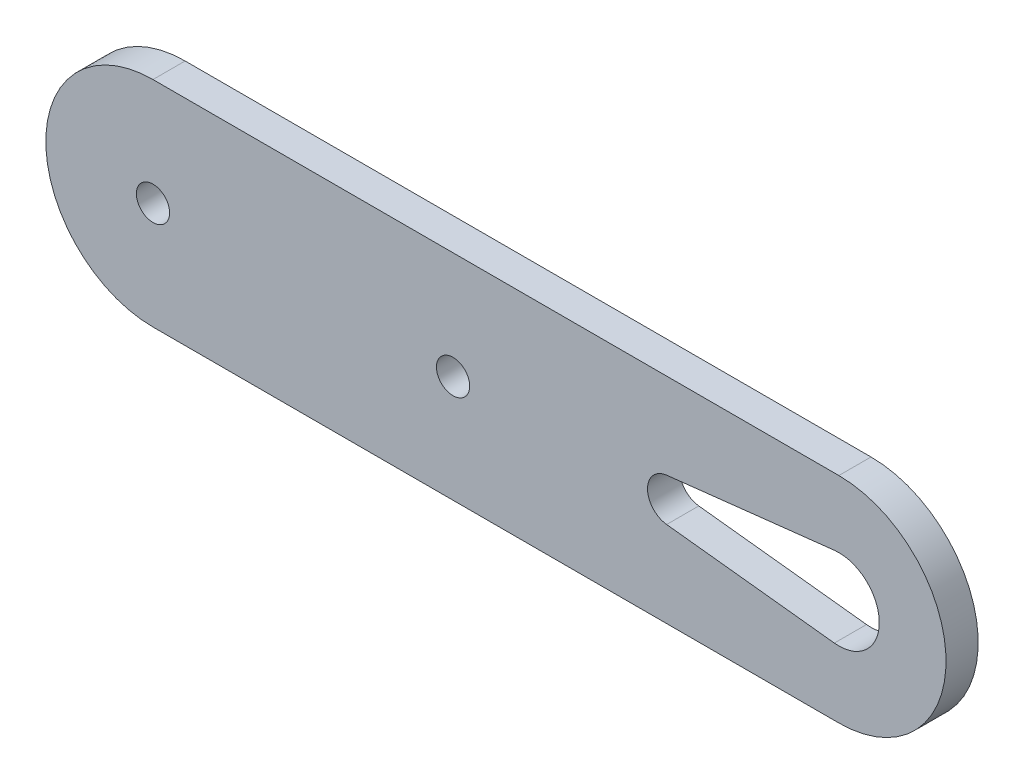
SolidWorks part; units mm, degrees
ref_plane "Front Plane" through (0, 0, 0) normal (0, 0, 1) x (1, 0, 0)
ref_plane "Top Plane" through (0, 0, 0) normal (0, 1, 0) x (1, 0, 0)
ref_plane "Right Plane" through (0, 0, 0) normal (1, 0, 0) x (0, 0, -1)
sketch "Sketch1" plane through (0, 0, 0) normal (0, 0, 1) x (1, 0, 0)
  line L0 (-58.0586, 14.1911) -> (5.9414, 14.1911) construction
  line L1 (-58.0586, 24.1911) -> (5.9414, 24.1911)
  line L2 (-58.0586, 4.1911) -> (5.9414, 4.1911)
  arc A0 (-58.0586, 24.1911) -> (-58.0586, 4.1911) centre (-58.0586, 14.1911) ccw
  arc A1 (5.9414, 4.1911) -> (5.9414, 24.1911) centre (5.9414, 14.1911) ccw
  point P2 (-26.0586, 14.1911)
extrude "Boss-Extrude1" add sketch "Sketch1" along normal blind 3
sketch "Sketch2" plane through (0, 0, 3) normal (0, 0, 1) x (1, 0, 0)
  line L1 (5.5203, 17.9411) -> (-10.1297, 16.1836)
  line L2 (5.5203, 10.4411) -> (-10.1297, 12.1986)
  arc A1 (5.5203, 17.9411) -> (5.5203, 10.4411) centre (5.9414, 14.1911) cw
  arc A2 (-10.1297, 16.1836) -> (-10.1297, 12.1986) centre (-9.906, 14.1911) ccw
  arc A3 (5.9414, 4.1911) -> (5.9414, 24.1911) centre (5.9414, 14.1911) ccw construction
  dimension "D1" = 7.5
  dimension "D2" = 3.985
  dimension "D3" = 15.65
  dimension "D4" = 15.65
extrude "Cut-Extrude1" cut sketch "Sketch2" against normal blind 3
sketch "Sketch4" plane through (9.9795, 1.4333, 3) normal (0, 0, 1) x (1, 0, 0)
  line L0 (-68.0381, 2.7578) -> (-4.0381, 2.7578) construction
  circle A0 centre (-40.0381, 12.7578) radius 1.55
  arc A2 (-4.0381, 2.7578) -> (-4.0381, 22.7578) centre (-4.0381, 12.7578) ccw construction
  dimension "D1" = 10
  dimension "D2" = 36
extrude "Cut-Extrude4" cut sketch "Sketch4" against normal blind 3
sketch "Sketch5" plane through (-9.9795, 1.4333, 0) normal (0, 0, -1) x (-1, 0, 0)
  line L0 (-15.9208, 22.7578) -> (48.0792, 22.7578) construction
  circle A0 centre (48.0792, 12.7578) radius 1.55
  circle A1 centre (20.0792, 12.7578) radius 1.55 construction
  dimension "D1" = 10
  dimension "D2" = 28
extrude "Cut-Extrude6" cut sketch "Sketch5" against normal blind 3
